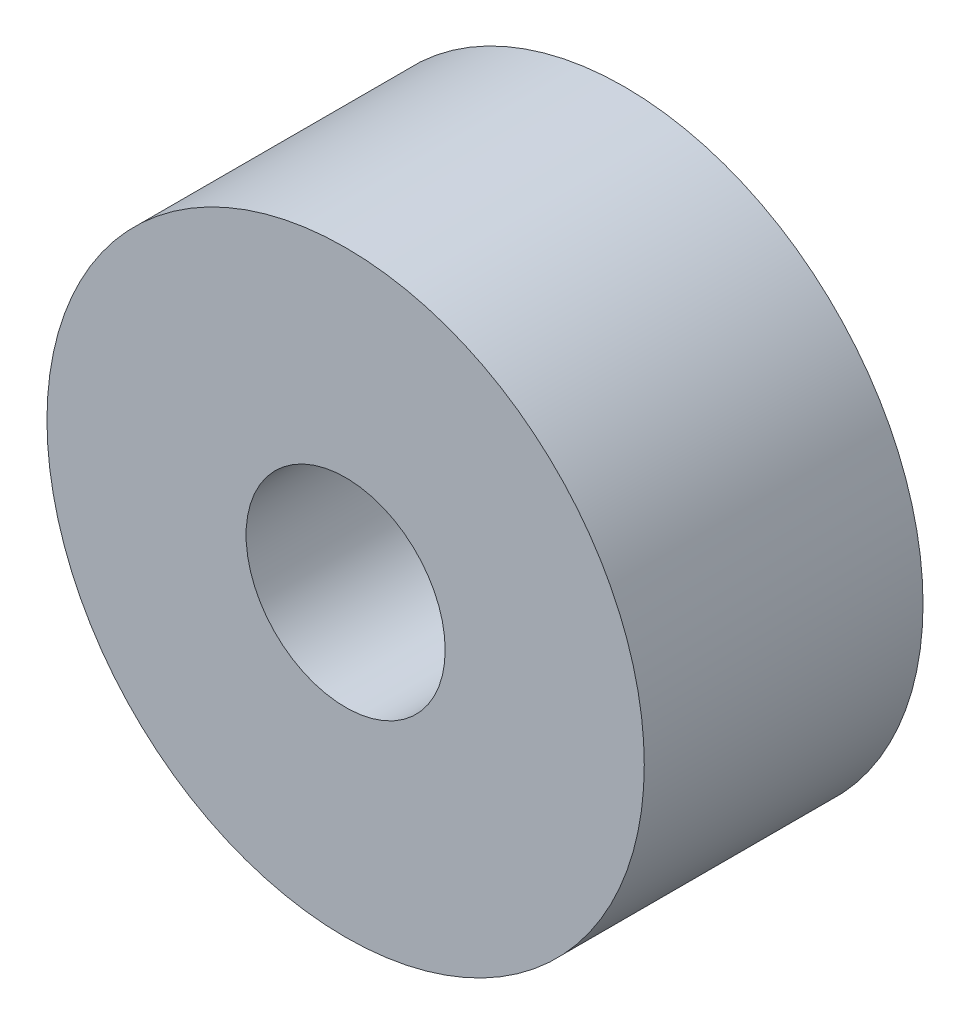
SolidWorks part; units mm, degrees
ref_plane "Płaszczyzna przednia" through (0, 0, 0) normal (0, 0, 1) x (1, 0, 0)
ref_plane "Płaszczyzna górna" through (0, 0, 0) normal (0, 1, 0) x (1, 0, 0)
ref_plane "Płaszczyzna prawa" through (0, 0, 0) normal (1, 0, 0) x (0, 0, -1)
sketch "Szkic1" plane through (0, 0, 0) normal (0, 0, 1) x (1, 0, 0)
  circle A0 centre (0, 0) radius 5
  circle A1 centre (0, 0) radius 15
  dimension "D1" = 10
  dimension "D2" = 30
extrude "Dodanie-wyciągnięcie1" add sketch "Szkic1" along normal blind 14
